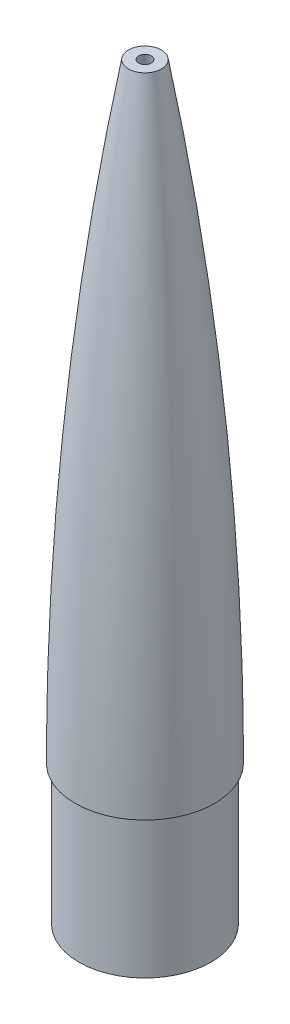
SolidWorks part; units mm, degrees
material "A-Glass Fiber"
ref_plane "Front Plane" through (0, 0, 0) normal (0, 0, 1) x (1, 0, 0)
ref_plane "Top Plane" through (0, 0, 0) normal (0, 1, 0) x (1, 0, 0)
ref_plane "Right Plane" through (0, 0, 0) normal (1, 0, 0) x (0, 0, -1)
sketch "Sketch1" plane through (0, 0, 0) normal (0, 0, 1) x (1, 0, 0)
  line L0 (0, 0) -> (-17.399, 0) construction
  line L2 (-17.399, 0) -> (-17.399, -40.64)
  line L3 (0, 203.2) -> (0, 0) construction
  line L6 (-1.8332, 177.8) -> (-4.7992, 177.8)
  line L7 (-1.8332, 177.8) -> (0, 177.8) construction
  line L9 (-19.2696, -40.64) -> (-19.2696, 0)
  line L10 (-19.2696, 0) -> (-20.32, 0)
  line L11 (-17.399, -40.64) -> (-19.2696, -40.64)
  arc A0 (-20.32, 0) -> (0, 203.2) centre (1005.84, 0) cw construction
  arc A1 (-17.399, 0) -> (0, 187.8934) centre (1005.84, 0) cw construction
  arc A6 (-4.7992, 177.8) -> (-20.32, 0) centre (1005.84, 0) ccw
  arc A7 (-1.8332, 177.8) -> (-17.399, 0) centre (1005.84, 0) ccw
  point P3 (0, 0)
  dimension "D1" = 20.32
  dimension "D2" = 17.399
  dimension "D3" = 203.2
  dimension "D4" = 25.4
  dimension "D5" = 19.2696
  dimension "D6" = 40.64
revolve "Revolve3" add sketch "Sketch1" angle 360 about L3
